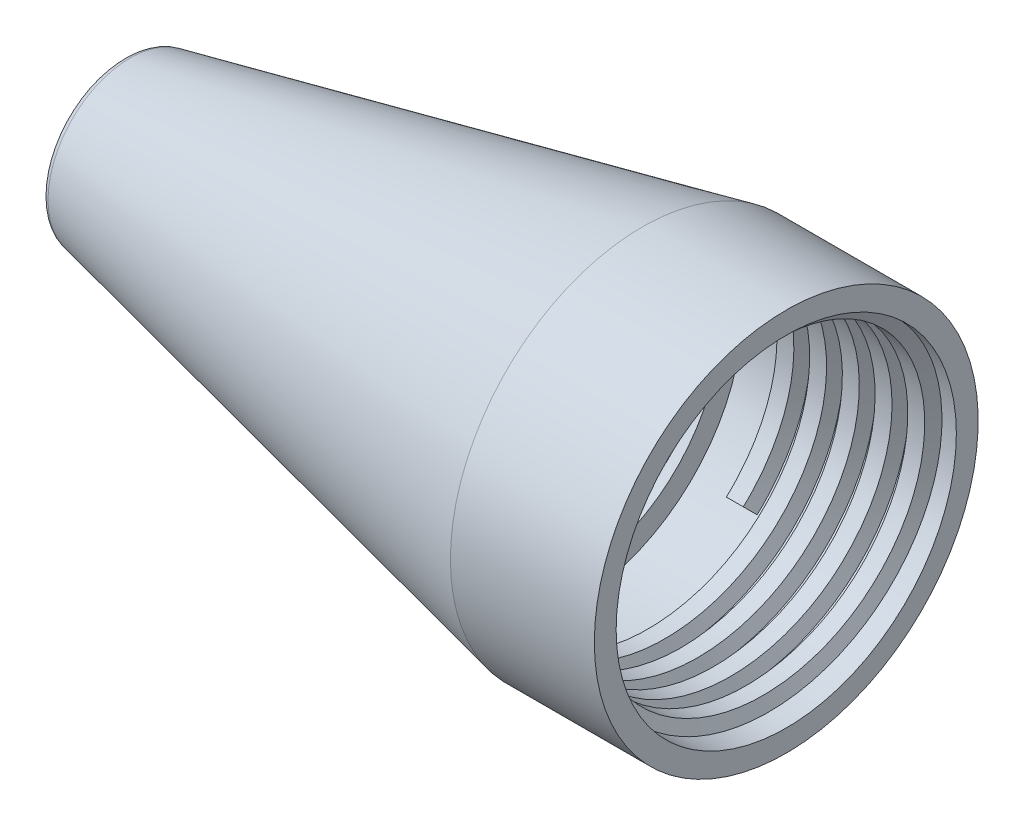
SolidWorks part; units mm, degrees
ref_plane "Plano frontal" through (0, 0, 0) normal (0, 0, 1) x (1, 0, 0)
ref_plane "Plano superior" through (0, 0, 0) normal (0, 1, 0) x (1, 0, 0)
ref_plane "Plano direito" through (0, 0, 0) normal (1, 0, 0) x (0, 0, -1)
sketch "Esboço1" plane through (0, 0, 0) normal (0, 0, 1) x (1, 0, 0)
  line L0 (0, 0) -> (15.2, 0) construction
  line L1 (2.14, 1.6282) -> (10.3, 3.3768)
  line L2 (15.2, 3.9) -> (10.3, 3.9)
  line L3 (11.9, 4.4) -> (0.1581, 1.8839)
  line L4 (0, 1.6883) -> (0, 1.2)
  line L5 (15.2, 4.4) -> (15.2, 3.9)
  line L6 (11.9, 4.4) -> (15.2, 4.4)
  line L7 (10.3, 3.3768) -> (10.3, 3.9)
  line L8 (0, 1.2) -> (2.14, 1.2)
  line L9 (2.14, 1.2) -> (2.14, 1.6282)
  arc A0 (0.1581, 1.8839) -> (0, 1.6883) centre (0.2, 1.6883) ccw
  point P12 (0, 1.85)
  dimension "D8" = 0.2
  dimension "D1" = 1.2
  dimension "D2" = 7.8
  dimension "D3" = 15.2
  dimension "D4" = 4.9
  dimension "D5" = 1.85
  dimension "D6" = 3.3
  dimension "D7" = 0.5
  dimension "D9" = 2.14
revolve "Revolução1" add sketch "Esboço1" angle 360 about L0
sketch "Esboço6" plane through (15.2, 0, 0) normal (1, 0, 0) x (0, 0, -1)
  circle A0 centre (0, 0) radius 3.9
curve "Hélice/Espiral2" pitch 0.75 height 3.375 turns 4.5
sketch "Esboço7" plane through (0, 0, 0) normal (0, 0, 1) x (1, 0, 0)
  line L0 (15.059, 3.9065) -> (14.9261, 3.6346)
  line L1 (14.4055, 3.9065) -> (14.5384, 3.6346)
  line L2 (14.4055, 4.0025) -> (14.4055, 3.9065)
  line L3 (14.9261, 3.6346) -> (14.5384, 3.6346)
  line L4 (14.4055, 4.0025) -> (15.059, 4.0025)
  line L5 (15.059, 4.0025) -> (15.059, 3.9065)
  line L6 (14.7322, 4.1017) -> (14.7322, 3.6635) construction
sweep "Varredura1" add profiles "Esboço7" path "Hélice/Espiral2"
